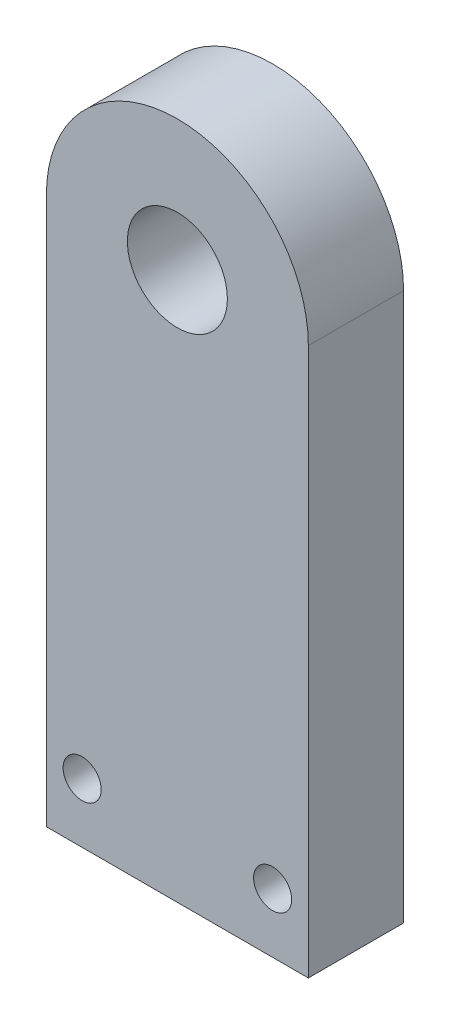
SolidWorks part; units mm, degrees
material "Liga 1060"
ref_plane "Plano frontal" through (0, 0, 0) normal (0, 0, 1) x (1, 0, 0)
ref_plane "Plano superior" through (0, 0, 0) normal (0, 1, 0) x (1, 0, 0)
ref_plane "Plano direito" through (0, 0, 0) normal (1, 0, 0) x (0, 0, -1)
sketch "Esboço1" plane through (0, 0, 0) normal (0, 0, 1) x (1, 0, 0)
  line L0 (-5.5, 0) -> (-5.5, -23)
  line L1 (5.5, 0) -> (5.5, -23)
  line L2 (5.5, -23) -> (-5.5, -23)
  arc A0 (5.5, 0) -> (-5.5, 0) centre (0, 0) ccw
  dimension "D1" = 11
  dimension "D2" = 23
extrude "Ressalto-extrusão1" add sketch "Esboço1" along normal blind 4
sketch "Esboço2" plane through (0, 0, 4) normal (0, 0, 1) x (1, 0, 0)
  circle A0 centre (0, 0) radius 3 construction
  point P3 (0, 3)
  point P11 (0, 0)
  dimension "D1" = 6
sketch "Esboço4" plane through (0, 0, 4) normal (0, 0, 1) x (1, 0, 0)
  line L0 (0, -23) -> (0, -20.5) construction
  line L1 (-5.5, -23) -> (5.5, -23) construction
  line L2 (-4, -20.5) -> (4, -20.5) construction
  dimension "D1" = 2.5
  dimension "D2" = 8
hole_wizard "Furo roscado de M21" positions "3DSketch3" profile "Esboço5" tap size "M2" standard "ISO" end condition through all
sketch3d "3DSketch3"
  point P0 (-4, -20.5, 4)
  point P6 (4, -20.5, 4)
sketch "Esboço5" plane through (-4, -20.5, 4) normal (1, 0, 0) x (0, -1, 0)
  line L0 (0, 0) -> (0, 4)
  line L1 (0, 4) -> (0.8, 4)
  line L2 (0.8, 4) -> (0.8, 0)
  line L5 (0.8, 0) -> (0, 0)
  line L11 (0, -6.35) -> (0, 107.95) construction
  dimension "Thru Tap Drill Dia." = 1.6
  dimension "Thru Tap Drill Depth" = 4
cosmetic thread "Rosca de furo1" parameters "D2"=2
cosmetic thread "Rosca de furo3" parameters "D2"=2
hole_wizard "Furo roscado para conduíte de M4x0.71" positions "Esboço6" profile "Esboço8" tap size "M4x0.7" standard "Helicoil® Metric" end condition through all
sketch "Esboço6" plane through (0, 0, 4) normal (0, 0, 1) x (1, 0, 0)
  point P0 (0, 0)
sketch "Esboço8" plane through (0, 0, 4) normal (1, 0, 0) x (0, -1, 0)
  line L0 (0, 0) -> (0, 4)
  line L1 (0, 4) -> (2.1, 4)
  line L2 (2.1, 4) -> (2.1, 0)
  line L5 (2.1, 0) -> (0, 0)
  line L11 (0, -6.35) -> (0, 107.95) construction
  dimension "Thru Tap Drill Dia." = 4.2
  dimension "Thru Tap Drill Depth" = 4
cosmetic thread "Rosca de furo4" parameters "D1"=4.7, "D2"=5.007
